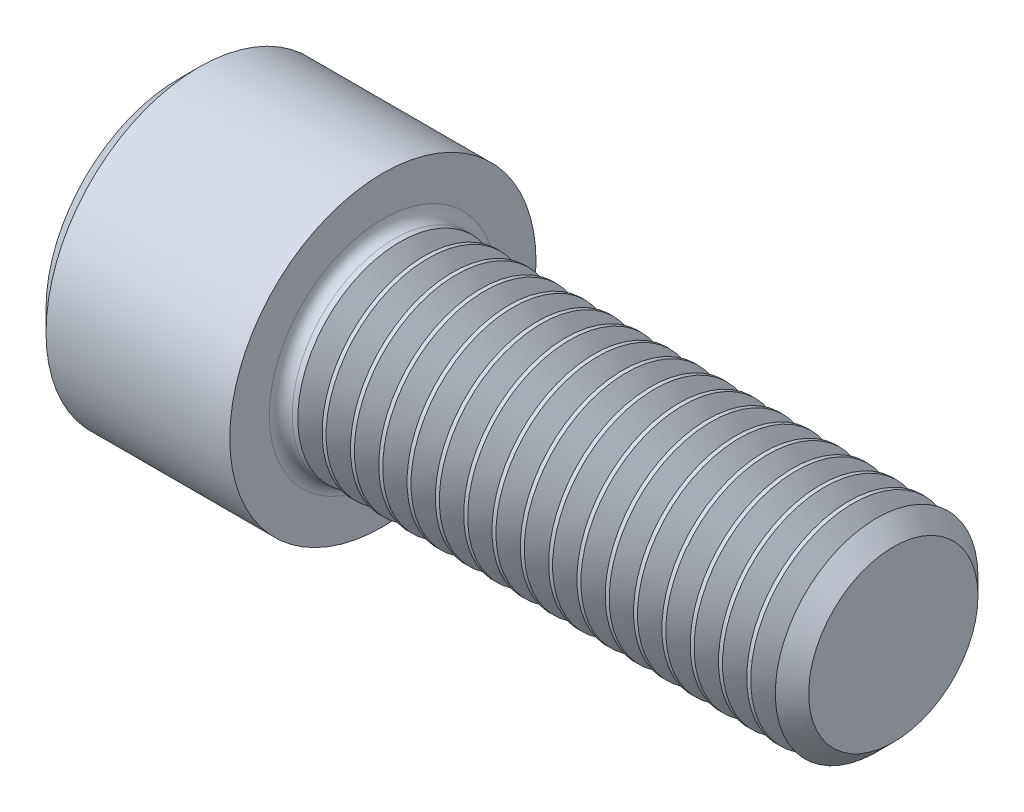
SolidWorks part; units mm, degrees
material "Chrome Stainless Steel"
ref_plane "Front Plane" through (0, 0, 0) normal (0, 0, 1) x (1, 0, 0)
ref_plane "Top Plane" through (0, 0, 0) normal (0, 1, 0) x (1, 0, 0)
ref_plane "Right Plane" through (0, 0, 0) normal (1, 0, 0) x (0, 0, -1)
ref_plane "Plane1" through (0, 0, 0) normal (0, 0, -1) x (-1, 0, 0)
sketch "Sketch1" plane through (0, 0, 0) normal (0, 0, -1) x (-1, 0, 0)
  line L0 (-6.35, 4.7625) -> (-6.35, 0)
  line L1 (-6.35, 0) -> (0, 0)
  line L2 (0, 0) -> (0, 4.7625)
  line L3 (0, 4.7625) -> (-6.35, 4.7625)
  line L4 (-6.35, 0) -> (0, 0) construction
revolve "Revolve1" add sketch "Sketch1" angle 360 about L4
sketch "Sketch2" plane through (6.35, 0, 0) normal (1, 0, 0) x (0, 0, -1)
  circle A0 centre (0, 0) radius 3.175
extrude "Boss-Extrude1" add sketch "Sketch2" along normal blind 0.528
sketch "Sketch3" plane through (6.878, 0, 0) normal (1, 0, 0) x (0, 0, -1)
  circle A0 centre (0, 0) radius 3.175
extrude "Boss-Extrude2" add sketch "Sketch3" along normal blind 0.3788 draft 55
sketch "Sketch4" plane through (7.2568, 0, 0) normal (1, 0, 0) x (0, 0, -1)
  circle A0 centre (0, 0) radius 2.634
extrude "Boss-Extrude3" add sketch "Sketch4" along normal blind 0.3788 draft 55 draft outward yes
sketch "Sketch5" plane through (7.6356, 0, 0) normal (1, 0, 0) x (0, 0, -1)
  circle A0 centre (0, 0) radius 3.175
extrude "Boss-Extrude4" add sketch "Sketch5" along normal blind 0.1228
sketch "Sketch6" plane through (7.7584, 0, 0) normal (1, 0, 0) x (0, 0, -1)
  circle A0 centre (0, 0) radius 3.175
extrude "Boss-Extrude5" add sketch "Sketch6" along normal blind 0.3788 draft 55
sketch "Sketch7" plane through (8.1373, 0, 0) normal (1, 0, 0) x (0, 0, -1)
  circle A0 centre (0, 0) radius 2.634
extrude "Boss-Extrude6" add sketch "Sketch7" along normal blind 0.3788 draft 55 draft outward yes
sketch "Sketch8" plane through (8.5161, 0, 0) normal (1, 0, 0) x (0, 0, -1)
  circle A0 centre (0, 0) radius 3.175
extrude "Boss-Extrude7" add sketch "Sketch8" along normal blind 0.1228
sketch "Sketch9" plane through (8.6389, 0, 0) normal (1, 0, 0) x (0, 0, -1)
  circle A0 centre (0, 0) radius 3.175
extrude "Boss-Extrude8" add sketch "Sketch9" along normal blind 0.3788 draft 55
sketch "Sketch10" plane through (9.0177, 0, 0) normal (1, 0, 0) x (0, 0, -1)
  circle A0 centre (0, 0) radius 2.634
extrude "Boss-Extrude9" add sketch "Sketch10" along normal blind 0.3788 draft 55 draft outward yes
sketch "Sketch11" plane through (9.3966, 0, 0) normal (1, 0, 0) x (0, 0, -1)
  circle A0 centre (0, 0) radius 3.175
extrude "Boss-Extrude10" add sketch "Sketch11" along normal blind 0.1228
sketch "Sketch12" plane through (9.5194, 0, 0) normal (1, 0, 0) x (0, 0, -1)
  circle A0 centre (0, 0) radius 3.175
extrude "Boss-Extrude11" add sketch "Sketch12" along normal blind 0.3788 draft 55
sketch "Sketch13" plane through (9.8982, 0, 0) normal (1, 0, 0) x (0, 0, -1)
  circle A0 centre (0, 0) radius 2.634
extrude "Boss-Extrude12" add sketch "Sketch13" along normal blind 0.3788 draft 55 draft outward yes
sketch "Sketch14" plane through (10.2771, 0, 0) normal (1, 0, 0) x (0, 0, -1)
  circle A0 centre (0, 0) radius 3.175
extrude "Boss-Extrude13" add sketch "Sketch14" along normal blind 0.1228
sketch "Sketch15" plane through (10.3999, 0, 0) normal (1, 0, 0) x (0, 0, -1)
  circle A0 centre (0, 0) radius 3.175
extrude "Boss-Extrude14" add sketch "Sketch15" along normal blind 0.3788 draft 55
sketch "Sketch16" plane through (10.7787, 0, 0) normal (1, 0, 0) x (0, 0, -1)
  circle A0 centre (0, 0) radius 2.634
extrude "Boss-Extrude15" add sketch "Sketch16" along normal blind 0.3788 draft 55 draft outward yes
sketch "Sketch17" plane through (11.1575, 0, 0) normal (1, 0, 0) x (0, 0, -1)
  circle A0 centre (0, 0) radius 3.175
extrude "Boss-Extrude16" add sketch "Sketch17" along normal blind 0.1228
sketch "Sketch18" plane through (11.2804, 0, 0) normal (1, 0, 0) x (0, 0, -1)
  circle A0 centre (0, 0) radius 3.175
extrude "Boss-Extrude17" add sketch "Sketch18" along normal blind 0.3788 draft 55
sketch "Sketch19" plane through (11.6592, 0, 0) normal (1, 0, 0) x (0, 0, -1)
  circle A0 centre (0, 0) radius 2.634
extrude "Boss-Extrude18" add sketch "Sketch19" along normal blind 0.3788 draft 55 draft outward yes
sketch "Sketch20" plane through (12.038, 0, 0) normal (1, 0, 0) x (0, 0, -1)
  circle A0 centre (0, 0) radius 3.175
extrude "Boss-Extrude19" add sketch "Sketch20" along normal blind 0.1228
sketch "Sketch21" plane through (12.1609, 0, 0) normal (1, 0, 0) x (0, 0, -1)
  circle A0 centre (0, 0) radius 3.175
extrude "Boss-Extrude20" add sketch "Sketch21" along normal blind 0.3788 draft 55
sketch "Sketch22" plane through (12.5397, 0, 0) normal (1, 0, 0) x (0, 0, -1)
  circle A0 centre (0, 0) radius 2.634
extrude "Boss-Extrude21" add sketch "Sketch22" along normal blind 0.3788 draft 55 draft outward yes
sketch "Sketch23" plane through (12.9185, 0, 0) normal (1, 0, 0) x (0, 0, -1)
  circle A0 centre (0, 0) radius 3.175
extrude "Boss-Extrude22" add sketch "Sketch23" along normal blind 0.1228
sketch "Sketch24" plane through (13.0413, 0, 0) normal (1, 0, 0) x (0, 0, -1)
  circle A0 centre (0, 0) radius 3.175
extrude "Boss-Extrude23" add sketch "Sketch24" along normal blind 0.3788 draft 55
sketch "Sketch25" plane through (13.4202, 0, 0) normal (1, 0, 0) x (0, 0, -1)
  circle A0 centre (0, 0) radius 2.634
extrude "Boss-Extrude24" add sketch "Sketch25" along normal blind 0.3788 draft 55 draft outward yes
sketch "Sketch26" plane through (13.799, 0, 0) normal (1, 0, 0) x (0, 0, -1)
  circle A0 centre (0, 0) radius 3.175
extrude "Boss-Extrude25" add sketch "Sketch26" along normal blind 0.1228
sketch "Sketch27" plane through (13.9218, 0, 0) normal (1, 0, 0) x (0, 0, -1)
  circle A0 centre (0, 0) radius 3.175
extrude "Boss-Extrude26" add sketch "Sketch27" along normal blind 0.3788 draft 55
sketch "Sketch28" plane through (14.3006, 0, 0) normal (1, 0, 0) x (0, 0, -1)
  circle A0 centre (0, 0) radius 2.634
extrude "Boss-Extrude27" add sketch "Sketch28" along normal blind 0.3788 draft 55 draft outward yes
sketch "Sketch29" plane through (14.6795, 0, 0) normal (1, 0, 0) x (0, 0, -1)
  circle A0 centre (0, 0) radius 3.175
extrude "Boss-Extrude28" add sketch "Sketch29" along normal blind 0.1228
sketch "Sketch30" plane through (14.8023, 0, 0) normal (1, 0, 0) x (0, 0, -1)
  circle A0 centre (0, 0) radius 3.175
extrude "Boss-Extrude29" add sketch "Sketch30" along normal blind 0.3788 draft 55
sketch "Sketch31" plane through (15.1811, 0, 0) normal (1, 0, 0) x (0, 0, -1)
  circle A0 centre (0, 0) radius 2.634
extrude "Boss-Extrude30" add sketch "Sketch31" along normal blind 0.3788 draft 55 draft outward yes
sketch "Sketch32" plane through (15.56, 0, 0) normal (1, 0, 0) x (0, 0, -1)
  circle A0 centre (0, 0) radius 3.175
extrude "Boss-Extrude31" add sketch "Sketch32" along normal blind 0.1228
sketch "Sketch33" plane through (15.6828, 0, 0) normal (1, 0, 0) x (0, 0, -1)
  circle A0 centre (0, 0) radius 3.175
extrude "Boss-Extrude32" add sketch "Sketch33" along normal blind 0.3788 draft 55
sketch "Sketch34" plane through (16.0616, 0, 0) normal (1, 0, 0) x (0, 0, -1)
  circle A0 centre (0, 0) radius 2.634
extrude "Boss-Extrude33" add sketch "Sketch34" along normal blind 0.3788 draft 55 draft outward yes
sketch "Sketch35" plane through (16.4404, 0, 0) normal (1, 0, 0) x (0, 0, -1)
  circle A0 centre (0, 0) radius 3.175
extrude "Boss-Extrude34" add sketch "Sketch35" along normal blind 0.1228
sketch "Sketch36" plane through (16.5633, 0, 0) normal (1, 0, 0) x (0, 0, -1)
  circle A0 centre (0, 0) radius 3.175
extrude "Boss-Extrude35" add sketch "Sketch36" along normal blind 0.3788 draft 55
sketch "Sketch37" plane through (16.9421, 0, 0) normal (1, 0, 0) x (0, 0, -1)
  circle A0 centre (0, 0) radius 2.634
extrude "Boss-Extrude36" add sketch "Sketch37" along normal blind 0.3788 draft 55 draft outward yes
sketch "Sketch38" plane through (17.3209, 0, 0) normal (1, 0, 0) x (0, 0, -1)
  circle A0 centre (0, 0) radius 3.175
extrude "Boss-Extrude37" add sketch "Sketch38" along normal blind 0.1228
sketch "Sketch39" plane through (17.4438, 0, 0) normal (1, 0, 0) x (0, 0, -1)
  circle A0 centre (0, 0) radius 3.175
extrude "Boss-Extrude38" add sketch "Sketch39" along normal blind 0.3788 draft 55
sketch "Sketch40" plane through (17.8226, 0, 0) normal (1, 0, 0) x (0, 0, -1)
  circle A0 centre (0, 0) radius 2.634
extrude "Boss-Extrude39" add sketch "Sketch40" along normal blind 0.3788 draft 55 draft outward yes
sketch "Sketch41" plane through (18.2014, 0, 0) normal (1, 0, 0) x (0, 0, -1)
  circle A0 centre (0, 0) radius 3.175
extrude "Boss-Extrude40" add sketch "Sketch41" along normal blind 0.1228
sketch "Sketch42" plane through (18.3242, 0, 0) normal (1, 0, 0) x (0, 0, -1)
  circle A0 centre (0, 0) radius 3.175
extrude "Boss-Extrude41" add sketch "Sketch42" along normal blind 0.3788 draft 55
sketch "Sketch43" plane through (18.7031, 0, 0) normal (1, 0, 0) x (0, 0, -1)
  circle A0 centre (0, 0) radius 2.634
extrude "Boss-Extrude42" add sketch "Sketch43" along normal blind 0.3788 draft 55 draft outward yes
sketch "Sketch44" plane through (19.0819, 0, 0) normal (1, 0, 0) x (0, 0, -1)
  circle A0 centre (0, 0) radius 3.175
extrude "Boss-Extrude43" add sketch "Sketch44" along normal blind 0.1228
sketch "Sketch45" plane through (19.2047, 0, 0) normal (1, 0, 0) x (0, 0, -1)
  circle A0 centre (0, 0) radius 3.175
extrude "Boss-Extrude44" add sketch "Sketch45" along normal blind 0.3788 draft 55
sketch "Sketch46" plane through (19.5835, 0, 0) normal (1, 0, 0) x (0, 0, -1)
  circle A0 centre (0, 0) radius 2.634
extrude "Boss-Extrude45" add sketch "Sketch46" along normal blind 0.3788 draft 55 draft outward yes
sketch "Sketch47" plane through (19.9624, 0, 0) normal (1, 0, 0) x (0, 0, -1)
  circle A0 centre (0, 0) radius 3.175
extrude "Boss-Extrude46" add sketch "Sketch47" along normal blind 0.1228
sketch "Sketch48" plane through (20.0852, 0, 0) normal (1, 0, 0) x (0, 0, -1)
  circle A0 centre (0, 0) radius 3.175
extrude "Boss-Extrude47" add sketch "Sketch48" along normal blind 0.3788 draft 55
sketch "Sketch49" plane through (20.464, 0, 0) normal (1, 0, 0) x (0, 0, -1)
  circle A0 centre (0, 0) radius 2.634
extrude "Boss-Extrude48" add sketch "Sketch49" along normal blind 0.3788 draft 55 draft outward yes
sketch "Sketch50" plane through (20.8429, 0, 0) normal (1, 0, 0) x (0, 0, -1)
  circle A0 centre (0, 0) radius 3.175
extrude "Boss-Extrude49" add sketch "Sketch50" along normal blind 0.1228
sketch "Sketch51" plane through (20.9657, 0, 0) normal (1, 0, 0) x (0, 0, -1)
  circle A0 centre (0, 0) radius 3.175
extrude "Boss-Extrude50" add sketch "Sketch51" along normal blind 0.3788 draft 55
sketch "Sketch52" plane through (21.3445, 0, 0) normal (1, 0, 0) x (0, 0, -1)
  circle A0 centre (0, 0) radius 2.634
extrude "Boss-Extrude51" add sketch "Sketch52" along normal blind 0.3626 draft 55 draft outward yes
sketch "Sketch53" plane through (21.7071, 0, 0) normal (1, 0, 0) x (0, 0, -1)
  circle A0 centre (0, 0) radius 3.1518
extrude "Boss-Extrude52" add sketch "Sketch53" along normal blind 0.5179 draft 45
sketch "Sketch54" plane through (0, 0, 0) normal (-1, 0, 0) x (0, 0, 1)
  line L0 (-2.3812, -1.3748) -> (0, -2.7496)
  line L1 (0, -2.7496) -> (2.3812, -1.3748)
  line L2 (2.3812, -1.3748) -> (2.3812, 1.3748)
  line L3 (2.3812, 1.3748) -> (0, 2.7496)
  line L4 (0, 2.7496) -> (-2.3813, 1.3748)
  line L5 (-2.3813, 1.3748) -> (-2.3812, -1.3748)
extrude "Cut-Extrude1" cut sketch "Sketch54" against normal blind 3.048
sketch "Sketch55" plane through (0, 0, 0) normal (0, 0, 1) x (1, 0, 0)
  line L0 (3.048, 2.3813) -> (3.048, 0)
  line L1 (3.048, 0) -> (4.4228, 0)
  line L2 (4.4228, 0) -> (3.048, 2.3813)
  line L3 (3.048, 0) -> (4.4229, 0) construction
revolve "Cut-Revolve1" cut sketch "Sketch55" angle 360 about L3
chamfer "Chamfer1" distance 0.635 angle 45 1 edges at (0, 0, 4.7625)
fillet "Fillet1" radius 0.3556 1 edges at (6.35, 0, -3.175)
